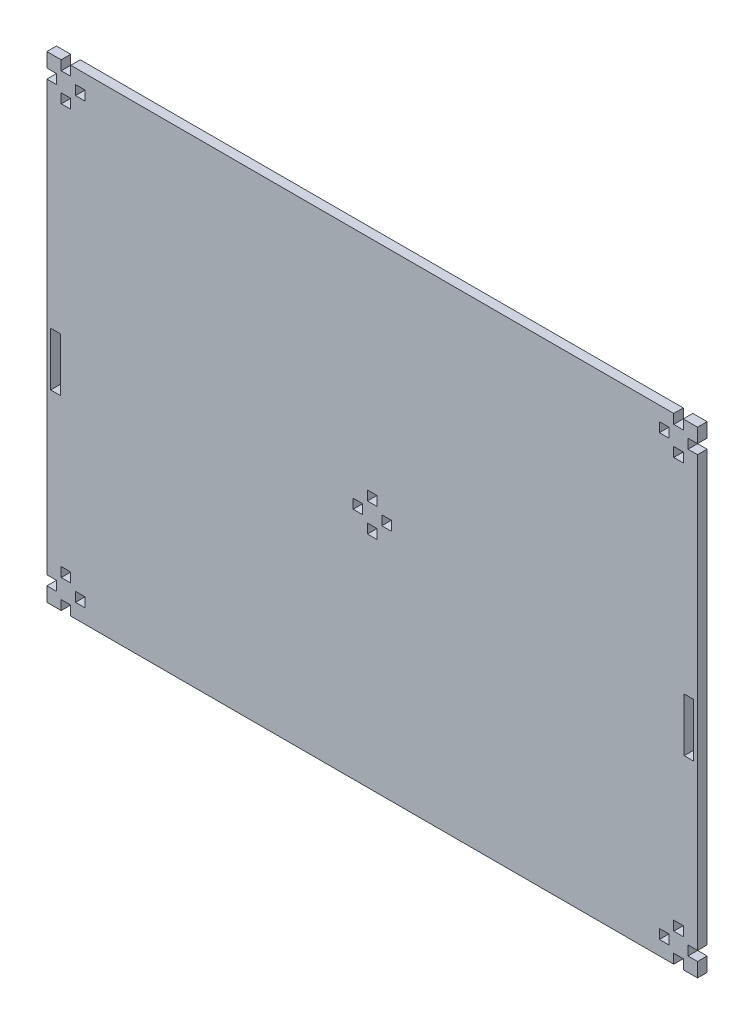
SolidWorks part; units mm, degrees
ref_plane "Front Plane" through (0, 0, 0) normal (0, 0, 1) x (1, 0, 0)
ref_plane "Top Plane" through (0, 0, 0) normal (0, 1, 0) x (1, 0, 0)
ref_plane "Right Plane" through (0, 0, 0) normal (1, 0, 0) x (0, 0, -1)
sketch "Sketch1" plane through (0, 0, 0) normal (0, 0, 1) x (1, 0, 0)
  line L0 (160.5, -240) -> (160.5, -79.3542) construction
  line L1 (331, 10) -> (323.5, 10)
  line L2 (331, 10) -> (331, 2.5)
  line L3 (331, -240) -> (323.5, -240)
  line L4 (-10, 10) -> (-10, 2.5)
  line L5 (-3, -114.6) -> (-8, -114.6)
  line L6 (-3, -114.6) -> (-3, -142.6)
  line L7 (-3, -142.6) -> (-8, -142.6)
  line L8 (-8, -114.6) -> (-8, -142.6)
  line L9 (329, -114.6) -> (329, -142.6)
  line L10 (324, -142.6) -> (329, -142.6)
  line L11 (324, -114.6) -> (324, -142.6)
  line L12 (324, -114.6) -> (329, -114.6)
  line L13 (318.5, 5) -> (323.5, 5) construction
  line L14 (323.5, 5) -> (323.5, 10) construction
  line L15 (-10, -2.5) -> (-10, -227.5)
  line L16 (318.5, 10) -> (318.5, 5) construction
  line L17 (316, -2.5) -> (316, 2.5) construction
  line L18 (316, 2.5) -> (311, 2.5) construction
  line L19 (311, 2.5) -> (311, -2.5) construction
  line L20 (311, -2.5) -> (316, -2.5) construction
  line L21 (318.5, -10) -> (323.5, -10) construction
  line L22 (323.5, -10) -> (323.5, -5) construction
  line L23 (323.5, -5) -> (318.5, -5) construction
  line L24 (318.5, -5) -> (318.5, -10) construction
  line L25 (-2.5, 10) -> (-10, 10)
  line L26 (331, 2.5) -> (326, 2.5) construction
  line L27 (326, 2.5) -> (326, -2.5) construction
  line L28 (326, -2.5) -> (331, -2.5) construction
  line L29 (2.5, -5) -> (-2.5, -5) construction
  line L30 (-2.5, -5) -> (-2.5, -10) construction
  line L31 (-2.5, -10) -> (2.5, -10) construction
  line L32 (2.5, -10) -> (2.5, -5) construction
  line L33 (5, 2.5) -> (5, -2.5) construction
  line L34 (5, -2.5) -> (10, -2.5) construction
  line L35 (10, -2.5) -> (10, 2.5) construction
  line L36 (10, 2.5) -> (5, 2.5) construction
  line L38 (-10, -2.5) -> (-5, -2.5) construction
  line L39 (-5, -2.5) -> (-5, 2.5) construction
  line L40 (-5, 2.5) -> (-10, 2.5) construction
  line L42 (-2.5, 10) -> (-2.5, 5) construction
  line L43 (-2.5, 5) -> (2.5, 5) construction
  line L44 (2.5, 5) -> (2.5, 10) construction
  line L45 (158, -125) -> (163, -125) construction
  line L46 (163, -125) -> (163, -120) construction
  line L47 (163, -120) -> (158, -120) construction
  line L48 (158, -120) -> (158, -125) construction
  line L49 (165.5, -112.5) -> (165.5, -117.5) construction
  line L50 (165.5, -117.5) -> (170.5, -117.5) construction
  line L51 (170.5, -117.5) -> (170.5, -112.5) construction
  line L52 (170.5, -112.5) -> (165.5, -112.5) construction
  line L53 (150.5, -112.5) -> (150.5, -117.5) construction
  line L54 (150.5, -117.5) -> (155.5, -117.5) construction
  line L55 (155.5, -117.5) -> (155.5, -112.5) construction
  line L56 (155.5, -112.5) -> (150.5, -112.5) construction
  line L57 (158, -110) -> (163, -110) construction
  line L58 (163, -110) -> (163, -105) construction
  line L59 (163, -105) -> (158, -105) construction
  line L60 (158, -105) -> (158, -110) construction
  line L61 (318.5, 5) -> (323.5, 5)
  line L62 (323.5, 5) -> (323.5, 10)
  line L64 (318.5, 10) -> (318.5, 5)
  line L65 (316, -2.5) -> (316, 2.5)
  line L66 (316, 2.5) -> (311, 2.5)
  line L67 (311, 2.5) -> (311, -2.5)
  line L68 (311, -2.5) -> (316, -2.5)
  line L69 (318.5, -10) -> (323.5, -10)
  line L70 (323.5, -10) -> (323.5, -5)
  line L71 (323.5, -5) -> (318.5, -5)
  line L72 (318.5, -5) -> (318.5, -10)
  line L74 (331, 2.5) -> (326, 2.5)
  line L75 (326, 2.5) -> (326, -2.5)
  line L76 (326, -2.5) -> (331, -2.5)
  line L77 (2.5, -5) -> (-2.5, -5)
  line L78 (-2.5, -5) -> (-2.5, -10)
  line L79 (-2.5, -10) -> (2.5, -10)
  line L80 (2.5, -10) -> (2.5, -5)
  line L81 (5, 2.5) -> (5, -2.5)
  line L82 (5, -2.5) -> (10, -2.5)
  line L83 (10, -2.5) -> (10, 2.5)
  line L84 (10, 2.5) -> (5, 2.5)
  line L86 (-10, -2.5) -> (-5, -2.5)
  line L87 (-5, -2.5) -> (-5, 2.5)
  line L88 (-5, 2.5) -> (-10, 2.5)
  line L90 (-2.5, 10) -> (-2.5, 5)
  line L91 (-2.5, 5) -> (2.5, 5)
  line L92 (2.5, 5) -> (2.5, 10)
  line L93 (158, -125) -> (163, -125)
  line L94 (163, -125) -> (163, -120)
  line L95 (163, -120) -> (158, -120)
  line L96 (158, -120) -> (158, -125)
  line L97 (165.5, -112.5) -> (165.5, -117.5)
  line L98 (165.5, -117.5) -> (170.5, -117.5)
  line L99 (170.5, -117.5) -> (170.5, -112.5)
  line L100 (170.5, -112.5) -> (165.5, -112.5)
  line L101 (150.5, -112.5) -> (150.5, -117.5)
  line L102 (150.5, -117.5) -> (155.5, -117.5)
  line L103 (155.5, -117.5) -> (155.5, -112.5)
  line L104 (155.5, -112.5) -> (150.5, -112.5)
  line L105 (158, -110) -> (163, -110)
  line L106 (163, -110) -> (163, -105)
  line L107 (163, -105) -> (158, -105)
  line L108 (158, -105) -> (158, -110)
  line L109 (331, -115) -> (225.9297, -115) construction
  line L110 (331, -2.5) -> (331, -227.5)
  line L111 (318.5, 10) -> (2.5, 10)
  line L112 (2.5, -235) -> (2.5, -240)
  line L113 (-2.5, -235) -> (2.5, -235)
  line L114 (-2.5, -240) -> (-2.5, -235)
  line L115 (-5, -232.5) -> (-10, -232.5)
  line L116 (-5, -227.5) -> (-5, -232.5)
  line L117 (-10, -227.5) -> (-5, -227.5)
  line L118 (10, -232.5) -> (5, -232.5)
  line L119 (10, -227.5) -> (10, -232.5)
  line L120 (5, -227.5) -> (10, -227.5)
  line L121 (5, -232.5) -> (5, -227.5)
  line L122 (2.5, -220) -> (2.5, -225)
  line L123 (-2.5, -220) -> (2.5, -220)
  line L124 (-2.5, -225) -> (-2.5, -220)
  line L125 (2.5, -225) -> (-2.5, -225)
  line L126 (326, -227.5) -> (331, -227.5)
  line L127 (326, -232.5) -> (326, -227.5)
  line L128 (331, -232.5) -> (326, -232.5)
  line L129 (318.5, -225) -> (318.5, -220)
  line L130 (323.5, -225) -> (318.5, -225)
  line L131 (323.5, -220) -> (323.5, -225)
  line L132 (318.5, -220) -> (323.5, -220)
  line L133 (311, -227.5) -> (316, -227.5)
  line L134 (311, -232.5) -> (311, -227.5)
  line L135 (316, -232.5) -> (311, -232.5)
  line L136 (316, -227.5) -> (316, -232.5)
  line L137 (318.5, -240) -> (318.5, -235)
  line L138 (323.5, -235) -> (323.5, -240)
  line L139 (318.5, -235) -> (323.5, -235)
  line L140 (331, -232.5) -> (331, -240)
  line L141 (318.5, -240) -> (2.5, -240)
  line L142 (-10, -232.5) -> (-10, -240)
  line L143 (-2.5, -240) -> (-10, -240)
extrude "Boss-Extrude1" add sketch "Sketch1" along normal blind 5
